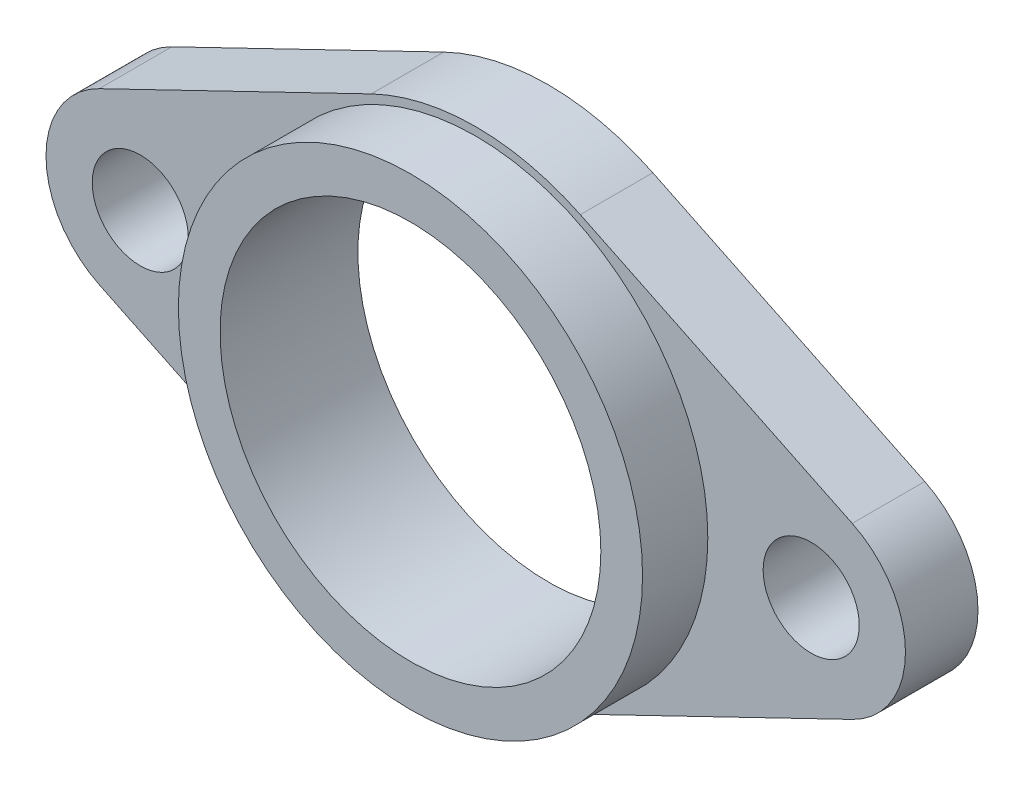
SolidWorks part; units mm, degrees
ref_plane "Front Plane" through (0, 0, 0) normal (0, 0, 1) x (1, 0, 0)
ref_plane "Top Plane" through (0, 0, 0) normal (0, 1, 0) x (1, 0, 0)
ref_plane "Right Plane" through (0, 0, 0) normal (1, 0, 0) x (0, 0, -1)
sketch "Layout Sketch" plane through (0, 0, 0) normal (0, 0, 1) x (1, 0, 0)
  line L0 (0, 0) -> (0, 14.778) construction
  circle A0 centre (-18.5, 0) radius 1 construction
  circle A1 centre (18.5, 0) radius 1 construction
  dimension "D1" = 2
  dimension "D2" = 37
sketch "Base Sketch" plane through (0, 0, 0) normal (0, 0, 1) x (1, 0, 0)
  line L0 (-20.7627, 4.6819) -> (-5.7655, 11.9298)
  line L1 (-20.7627, -4.6819) -> (-5.7655, -11.9298)
  line L2 (5.7655, 11.9298) -> (20.7627, 4.6819)
  line L3 (20.7627, -4.6819) -> (5.7655, -11.9298)
  line L4 (0, 0) -> (7.7453, 0) construction
  arc A0 (-20.7627, 4.6819) -> (-20.7627, -4.6819) centre (-18.5, 0) ccw
  arc A1 (20.7627, -4.6819) -> (20.7627, 4.6819) centre (18.5, 0) ccw
  arc A2 (-5.7655, -11.9298) -> (5.7655, -11.9298) centre (0, 0) ccw
  arc A3 (5.7655, 11.9298) -> (-5.7655, 11.9298) centre (0, 0) ccw
  circle A4 centre (0, 0) radius 10.5
  dimension "D1" = 26.5
  dimension "D2" = 5.2
  dimension "D3" = 21
extrude "Base Extrude" add sketch "Base Sketch" along normal blind 4
sketch "Bearing Retaining Ring Sketch" plane through (0, 0, 0) normal (0, 0, 1) x (1, 0, 0)
  circle A0 centre (0, 0) radius 10.5
  circle A1 centre (0, 0) radius 12.8
  circle A3 centre (0, 0) radius 10.5 construction
  dimension "D1" = 25.6
extrude "Bearing Retaining Ring" add sketch "Bearing Retaining Ring Sketch" along normal blind 7.6
hole_wizard "Mounting Holes" positions "Mounting Holes Position Sketch" profile "Mounting Holes Profile Sketch" hole size "M5" standard "ANSI Metric" end condition up to next
sketch "Mounting Holes Position Sketch" plane through (0, 0, 0) normal (0, 0, -1) x (-1, 0, 0)
  point P0 (18.5, 0)
  point P3 (-18.5, 0)
sketch "Mounting Holes Profile Sketch" plane through (-18.5, 0, 0) normal (1, 0, 0) x (0, 1, 0)
  line L0 (0, 0) -> (0, 4)
  line L1 (0, 4) -> (2.65, 4)
  line L2 (2.65, 4) -> (2.65, 0)
  line L5 (2.65, 0) -> (0, 0)
  line L11 (0, -6.35) -> (0, 107.95) construction
  dimension "Thru Hole Dia." = 5.3
  dimension "Thru Hole Depth" = 4
